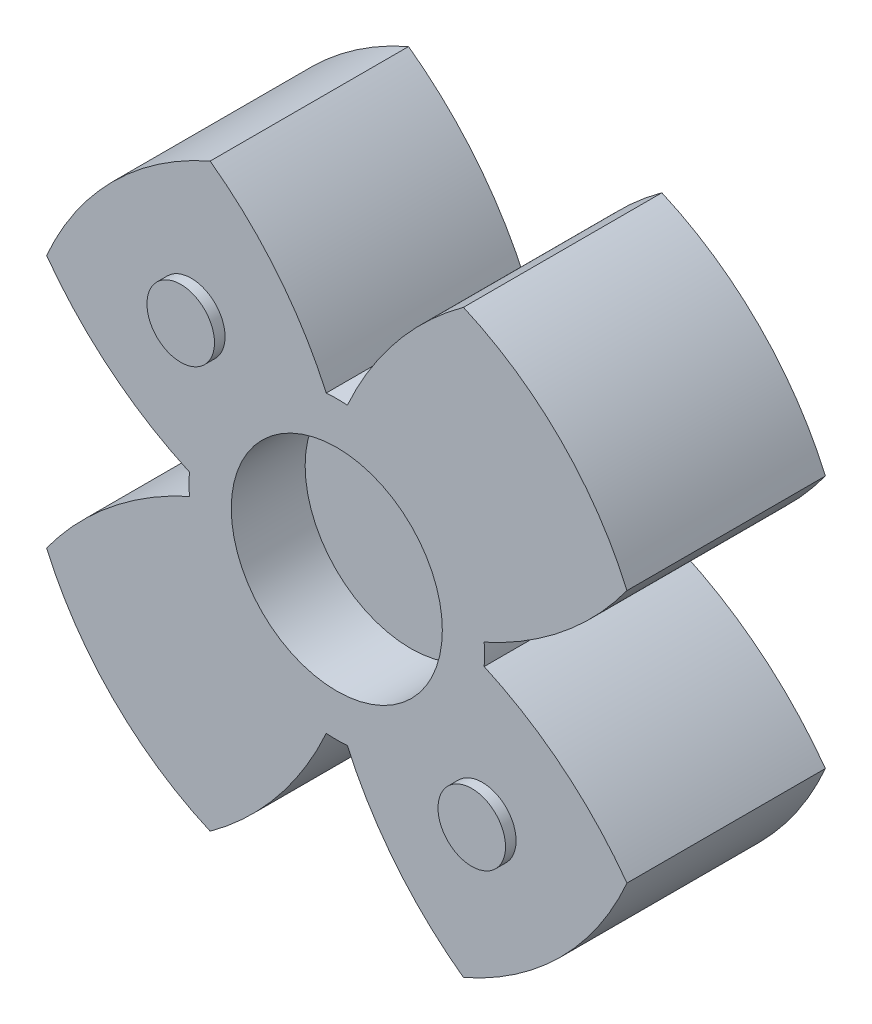
SolidWorks part; units mm, degrees
material "Rubber"
ref_plane "Front" through (0, 0, 0) normal (0, 0, 1) x (1, 0, 0)
ref_plane "Top" through (0, 0, 0) normal (0, 1, 0) x (1, 0, 0)
ref_plane "Right" through (0, 0, 0) normal (1, 0, 0) x (0, 0, -1)
sketch "Sketch1" plane through (0, 0, 0) normal (0, 0, 1) x (1, 0, 0)
  arc A2 (6, -13.7477) -> (13.7477, -6) centre (0, 0) ccw
  arc A4 (-6, -13.7477) -> (-0.5, -6.9821) centre (-16, 0) ccw
  arc A6 (-6.9821, -0.5) -> (-13.7477, -6) centre (0, -16) ccw
  arc A8 (-13.7477, 6) -> (-6.9821, 0.5) centre (0, 16) ccw
  arc A10 (-0.5, 6.9821) -> (-6, 13.7477) centre (-16, 0) ccw
  arc A12 (6, 13.7477) -> (0.5, 6.9821) centre (16, 0) ccw
  arc A14 (6.9821, 0.5) -> (13.7477, 6) centre (0, 16) ccw
  arc A16 (13.7477, -6) -> (6.9821, -0.5) centre (0, -16) ccw
  arc A18 (0.5, -6.9821) -> (6, -13.7477) centre (16, 0) ccw
  arc A19 (-6, 13.7477) -> (-13.7477, 6) centre (0, 0) ccw
  arc A20 (-13.7477, -6) -> (-6, -13.7477) centre (0, 0) ccw
  arc A21 (13.7477, 6) -> (6, 13.7477) centre (0, 0) ccw
  arc A23 (-0.5, -6.9821) -> (0.5, -6.9821) centre (0, 0) ccw
  arc A24 (6.9821, -0.5) -> (6.9821, 0.5) centre (0, 0) ccw
  arc A25 (0.5, 6.9821) -> (-0.5, 6.9821) centre (0, 0) ccw
  arc A26 (-6.9821, 0.5) -> (-6.9821, -0.5) centre (0, 0) ccw
  dimension "D2" = 30
extrude "Boss-Extrude1" add sketch "Sketch1" along normal blind 9.4
sketch "Sketch2" plane through (0, 0, 9.4) normal (0, 0, 1) x (1, 0, 0)
  circle A0 centre (0, 0) radius 5
extrude "Cut-Extrude1" cut sketch "Sketch2" against normal blind 3.5
sketch "Sketch3" plane through (0, 0, 0) normal (0, 0, -1) x (-1, 0, 0)
  circle A0 centre (0, 0) radius 5 construction
  circle A1 centre (0, 0) radius 5
extrude "Cut-Extrude2" cut sketch "Sketch3" against normal blind 3.5
sketch "Sketch4" plane through (0, 0, 9.4) normal (0, 0, 1) x (1, 0, 0)
  line L0 (0, 0) -> (9.75, 0) construction
  line L1 (0, 0) -> (6.8943, -6.8943) construction
  line L2 (0, 0) -> (-6.8943, 6.8943) construction
  circle A0 centre (0, 0) radius 9.75 construction
  circle A1 centre (-6.8943, 6.8943) radius 1.6
  circle A2 centre (6.8943, -6.8943) radius 1.6
  dimension "D1" = 19.5
  dimension "D2" = 45
extrude "Boss-Extrude2" add sketch "Sketch4" along normal blind 0.5
sketch "Sketch5" plane through (0, 0, 0) normal (0, 0, -1) x (-1, 0, 0)
  line L0 (0, 11.7042) -> (0, -2.0881) construction
  circle A0 centre (-6.8943, -6.8943) radius 1.6 construction
  circle A1 centre (-6.8943, -6.8943) radius 1.6 construction
  circle A2 centre (6.8943, 6.8943) radius 1.6 construction
  circle A3 centre (6.8943, 6.8943) radius 1.6 construction
  circle A4 centre (-6.8943, 6.8943) radius 1.6
  circle A5 centre (6.8943, -6.8943) radius 1.6
extrude "Boss-Extrude3" add sketch "Sketch5" along normal blind 0.5
